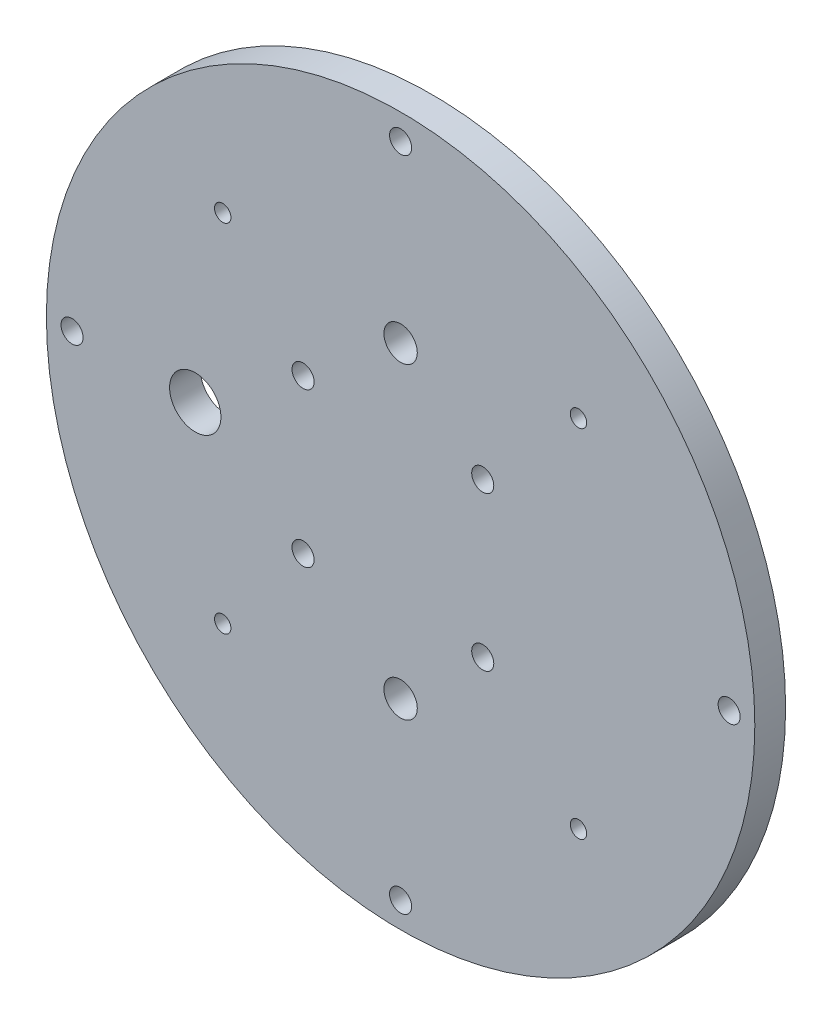
SolidWorks part; units mm, degrees
ref_plane "Front Plane" through (0, 0, 0) normal (0, 0, 1) x (1, 0, 0)
ref_plane "Top Plane" through (0, 0, 0) normal (0, 1, 0) x (1, 0, 0)
ref_plane "Right Plane" through (0, 0, 0) normal (1, 0, 0) x (0, 0, -1)
sketch "草圖1" plane through (0, 0, 0) normal (0, 0, 1) x (1, 0, 0)
  circle A0 centre (0, 0) radius 69
  circle A1 centre (34.6482, 34.6482) radius 1.6
  circle A2 centre (-34.6482, 34.6482) radius 1.6
  circle A3 centre (-34.6482, -34.6482) radius 1.6
  circle A4 centre (34.6482, -34.6482) radius 1.6
  circle A5 centre (64, 0) radius 2.15
  circle A6 centre (0, 64) radius 2.15
  circle A7 centre (-64, 0) radius 2.15
  circle A8 centre (0, -64) radius 2.15
  circle A9 centre (-19, 15) radius 2.15
  circle A10 centre (-19, -15) radius 2.15
  circle A11 centre (16, 15) radius 2.15
  circle A12 centre (16, -15) radius 2.15
  circle A13 centre (0, 30) radius 3.25
  circle A14 centre (0, -30) radius 3.25
  circle A15 centre (-40, 0) radius 5
extrude "填料-伸長1" add sketch "草圖1" along normal blind 6
